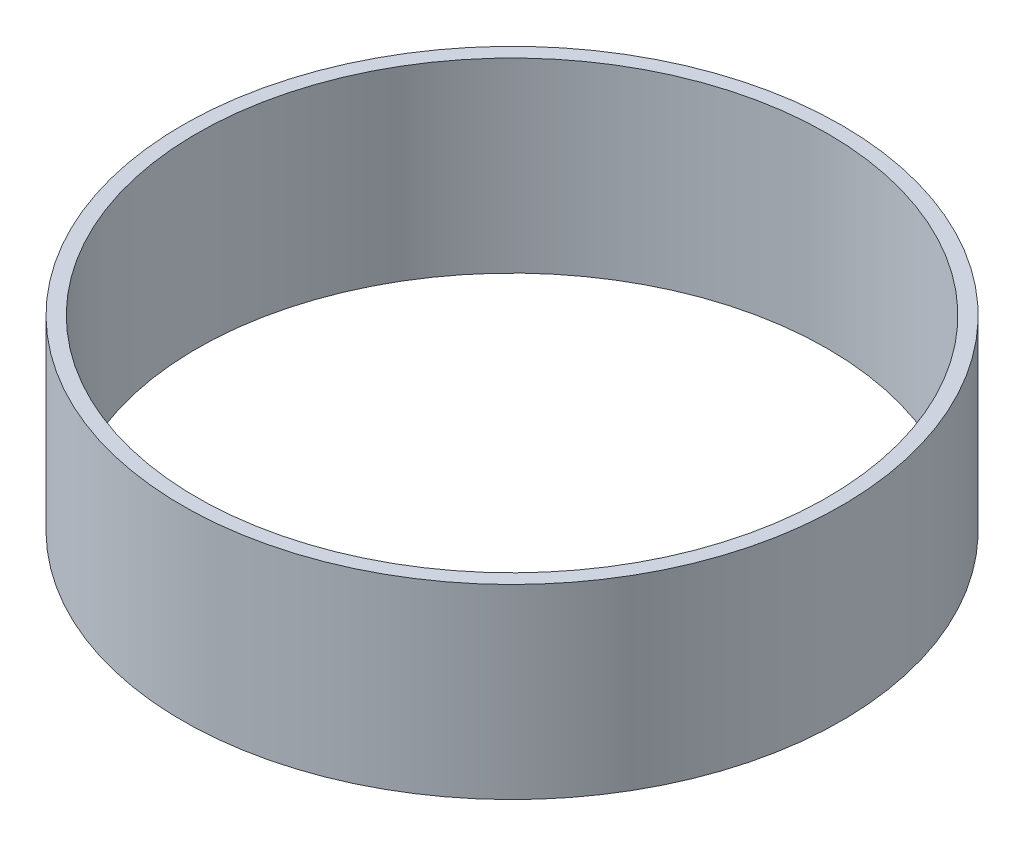
SolidWorks part; units mm, degrees
material "1.0038 (S235JRG2)"
ref_plane "Horní rovina" through (0, 0, 0) normal (0, 0, 1) x (1, 0, 0)
ref_plane "Přední rovina" through (0, 0, 0) normal (0, 1, 0) x (1, 0, 0)
ref_plane "Pravá rovina" through (0, 0, 0) normal (1, 0, 0) x (0, 0, -1)
sketch "Skica1" plane through (0, 0, 0) normal (0, 1, 0) x (1, 0, 0)
  circle A0 centre (0, 0) radius 44
  circle A1 centre (0, 0) radius 46
  dimension "D1" = 88
  dimension "D2" = 92
extrude "Přidat vysunutím1" add sketch "Skica1" along normal blind 26
